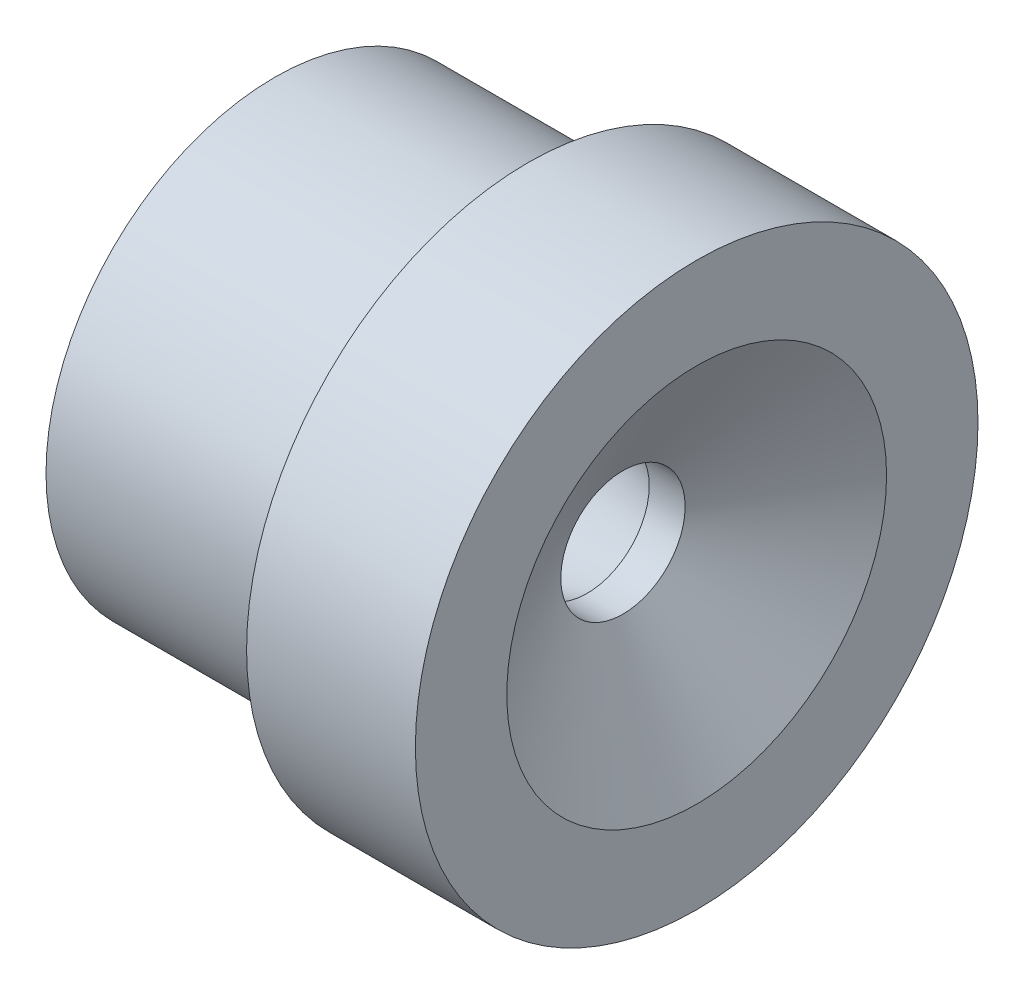
SolidWorks part; units mm, degrees
material "C (Graphite)"
ref_plane "Front Plane" through (0, 0, 0) normal (0, 0, 1) x (1, 0, 0)
ref_plane "Top Plane" through (0, 0, 0) normal (0, 1, 0) x (1, 0, 0)
ref_plane "Right Plane" through (0, 0, 0) normal (1, 0, 0) x (0, 0, -1)
sketch "Sketch1" plane through (0, 0, 0) normal (0, 1, 0) x (1, 0, 0)
  line L0 (0, 0) -> (0, 4.1275)
  line L1 (0, 4.1275) -> (-3.3289, 9.8933)
  line L2 (-3.3289, 9.8933) -> (-4.9494, 9.8933)
  line L3 (-4.9494, 9.8933) -> (-19.05, 6.1151)
  line L4 (-19.05, 6.1151) -> (-19.05, 2.3749)
  line L5 (-19.05, 2.3749) -> (-7.62, 2.3749)
  line L6 (-7.62, 2.3749) -> (-7.62, 0)
  line L9 (-7.62, 0) -> (0, 0)
  line L10 (5.1187, 12.7) -> (-11.0703, 12.7) construction
  dimension "D1" = 25.4
  dimension "D2" = 5.6134
  dimension "D3" = 60
  dimension "D4" = 15
  dimension "D5" = 17.145
  dimension "D6" = 1.6205
  dimension "D7" = 7.62
  dimension "D8" = 19.05
  dimension "D9" = 20.6502
revolve "Revolve1" add sketch "Sketch1" angle 360 about L10
